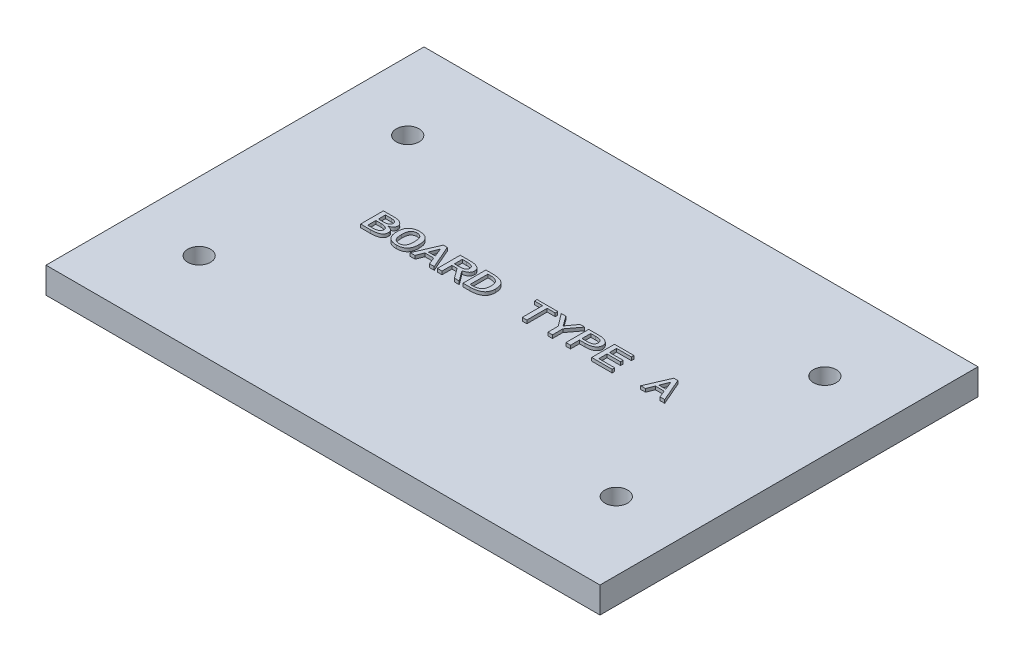
SolidWorks part; units mm, degrees
ref_plane "前视基准面" through (0, 0, 0) normal (0, 0, 1) x (1, 0, 0)
ref_plane "上视基准面" through (0, 0, 0) normal (0, 1, 0) x (1, 0, 0)
ref_plane "右视基准面" through (0, 0, 0) normal (1, 0, 0) x (0, 0, -1)
sketch "草图1" plane through (0, 0, 0) normal (0, 1, 0) x (1, 0, 0)
  line L1 (-42.5, 29) -> (42.5, 29)
  line L2 (-42.5, 29) -> (-42.5, -29)
  line L3 (-42.5, -29) -> (42.5, -29)
  line L4 (42.5, 29) -> (42.5, -29)
  line L5 (-42.5, 29) -> (23.4483, -16) construction
  line L11 (-30.4348, 15.2174) -> (0, 0) construction
  line L12 (-30.4348, -15.2174) -> (0, 0) construction
  circle A0 centre (-32, 16) radius 1.75
  circle A1 centre (32, 16) radius 1.75
  circle A2 centre (-32, -16) radius 1.75
  circle A3 centre (32, -16) radius 1.75
  point P0 (0, 0)
  point P6 (0, 0)
  dimension "D5" = 3.5
  dimension "D6" = 3.5
  dimension "D7" = 3.5
  dimension "D8" = 3.5
  dimension "D1" = 58
  dimension "D2" = 32
  dimension "D3" = 85
  dimension "D4" = 64
extrude "凸台-拉伸1" add sketch "草图1" along normal blind 4
sketch "草图2" plane through (0, 4, 0) normal (0, 1, 0) x (1, 0, 0)
  line L1 (-21.7977, 0.1023) -> (-23.3328, 0.1023)
  line L2 (-23.3328, 0.1023) -> (-23.3328, 3.6023)
  line L3 (-23.3328, 3.6023) -> (-21.7363, 3.6023)
  line L4 (-21.706, 3.2135) -> (-22.627, 3.2135)
  line L5 (-22.627, 3.2135) -> (-22.627, 2.1287)
  line L6 (-22.627, 2.1287) -> (-21.7363, 2.1287)
  line L7 (-21.8288, 1.7398) -> (-22.627, 1.7398)
  line L8 (-22.627, 1.7398) -> (-22.627, 0.4912)
  line L9 (-22.627, 0.4912) -> (-21.9205, 0.4912)
  line L10 (-12.0345, 0.1023) -> (-12.7714, 0.1023)
  line L11 (-12.7714, 0.1023) -> (-13.2012, 1.1871)
  line L12 (-13.2012, 1.1871) -> (-14.5521, 1.1871)
  line L13 (-14.5521, 1.1871) -> (-14.9819, 0.1023)
  line L14 (-14.9819, 0.1023) -> (-15.7187, 0.1023)
  line L15 (-15.7187, 0.1023) -> (-14.1837, 3.6433)
  line L16 (-14.1837, 3.6433) -> (-13.5696, 3.6433)
  line L17 (-13.5696, 3.6433) -> (-12.0345, 0.1023)
  line L18 (-13.3551, 1.576) -> (-13.8463, 2.8246)
  line L19 (-13.8463, 2.8246) -> (-13.9077, 2.8246)
  line L20 (-13.9077, 2.8246) -> (-14.3989, 1.576)
  line L21 (-14.3989, 1.576) -> (-13.3551, 1.576)
  line L22 (-8.1972, 0.1023) -> (-8.934, 0.1023)
  line L23 (-8.934, 0.1023) -> (-10.0393, 1.617)
  line L24 (-10.0393, 1.617) -> (-10.8375, 1.617)
  line L25 (-10.8375, 1.617) -> (-10.8375, 0.1023)
  line L26 (-10.8375, 0.1023) -> (-11.5433, 0.1023)
  line L27 (-11.5433, 0.1023) -> (-11.5433, 3.6023)
  line L28 (-11.5433, 3.6023) -> (-10.0082, 3.6023)
  line L29 (-9.3639, 1.6784) -> (-8.1972, 0.1023)
  line L30 (-10.1621, 3.2135) -> (-10.8375, 3.2135)
  line L31 (-10.8375, 3.2135) -> (-10.8375, 2.0058)
  line L32 (-10.8375, 2.0058) -> (-9.9779, 2.0058)
  line L33 (-6.5696, 0.1023) -> (-7.6135, 0.1023)
  line L34 (-7.6135, 0.1023) -> (-7.6135, 3.6023)
  line L35 (-7.6135, 3.6023) -> (-6.5696, 3.6023)
  line L36 (-6.5696, 3.2135) -> (-6.9077, 3.2135)
  line L37 (-6.9077, 3.2135) -> (-6.9077, 0.4912)
  line L38 (-6.9077, 0.4912) -> (-6.5696, 0.4912)
  line L39 (3.4081, 3.2135) -> (2.18, 3.2135)
  line L40 (2.18, 3.2135) -> (2.18, 0.1023)
  line L41 (2.18, 0.1023) -> (1.4742, 0.1023)
  line L42 (1.4742, 0.1023) -> (1.4742, 3.2135)
  line L43 (1.4742, 3.2135) -> (0.2462, 3.2135)
  line L44 (0.2462, 3.2135) -> (0.2462, 3.6023)
  line L45 (0.2462, 3.6023) -> (3.4081, 3.6023)
  line L46 (3.4081, 3.6023) -> (3.4081, 3.2135)
  line L47 (7.5532, 3.6023) -> (6.1098, 1.6784)
  line L48 (6.1098, 1.6784) -> (6.1098, 0.1023)
  line L49 (6.1098, 0.1023) -> (5.4041, 0.1023)
  line L50 (5.4041, 0.1023) -> (5.4041, 1.6784)
  line L51 (5.4041, 1.6784) -> (3.9607, 3.6023)
  line L52 (3.9607, 3.6023) -> (4.6672, 3.6023)
  line L53 (4.6672, 3.6023) -> (5.7414, 2.1082)
  line L54 (5.7414, 2.1082) -> (5.7725, 2.1082)
  line L55 (5.7725, 2.1082) -> (6.8467, 3.6023)
  line L56 (6.8467, 3.6023) -> (7.5532, 3.6023)
  line L57 (9.7637, 1.4737) -> (8.873, 1.4737)
  line L58 (8.873, 1.4737) -> (8.873, 0.1023)
  line L59 (8.873, 0.1023) -> (8.1672, 0.1023)
  line L60 (8.1672, 0.1023) -> (8.1672, 3.6023)
  line L61 (8.1672, 3.6023) -> (9.7637, 3.6023)
  line L62 (9.5795, 3.2135) -> (8.873, 3.2135)
  line L63 (8.873, 3.2135) -> (8.873, 1.8626)
  line L64 (8.873, 1.8626) -> (9.5795, 1.8626)
  line L65 (15.2589, 0.1023) -> (12.1274, 0.1023)
  line L66 (12.1274, 0.1023) -> (12.1274, 3.6023)
  line L67 (12.1274, 3.6023) -> (15.1058, 3.6023)
  line L68 (15.1058, 3.6023) -> (15.1058, 3.2135)
  line L69 (15.1058, 3.2135) -> (12.8339, 3.2135)
  line L70 (12.8339, 3.2135) -> (12.8339, 2.1287)
  line L71 (12.8339, 2.1287) -> (14.9216, 2.1287)
  line L72 (14.9216, 2.1287) -> (14.9216, 1.7398)
  line L73 (14.9216, 1.7398) -> (12.8339, 1.7398)
  line L74 (12.8339, 1.7398) -> (12.8339, 0.4912)
  line L75 (12.8339, 0.4912) -> (15.2589, 0.4912)
  line L76 (15.2589, 0.4912) -> (15.2589, 0.1023)
  line L77 (23.3339, 0.1023) -> (22.597, 0.1023)
  line L78 (22.597, 0.1023) -> (22.1672, 1.1871)
  line L79 (22.1672, 1.1871) -> (20.8163, 1.1871)
  line L80 (20.8163, 1.1871) -> (20.3865, 0.1023)
  line L81 (20.3865, 0.1023) -> (19.6497, 0.1023)
  line L82 (19.6497, 0.1023) -> (21.1848, 3.6433)
  line L83 (21.1848, 3.6433) -> (21.7988, 3.6433)
  line L84 (21.7988, 3.6433) -> (23.3339, 0.1023)
  line L85 (22.0133, 1.576) -> (21.5221, 2.8246)
  line L86 (21.5221, 2.8246) -> (21.4607, 2.8246)
  line L87 (21.4607, 2.8246) -> (20.9695, 1.576)
  line L88 (20.9695, 1.576) -> (22.0133, 1.576)
  spline S0 degree 3 poles (-20.0481, 1.1462) (-20.0483, 1.0544) (-20.0603, 0.9197) (-20.1134, 0.7533) (-20.168, 0.6439) (-20.2374, 0.5458) (-20.3231, 0.4597) (-20.4244, 0.3858) (-20.5405, 0.3245) (-20.6677, 0.2723) (-20.8038, 0.2269) (-20.9484, 0.1883) (-21.1015, 0.1565) (-21.2635, 0.1326) (-21.4962, 0.109) (-21.6755, 0.1026) (-21.7977, 0.1023) knots 0 0 0 0 0.119736 0.174373 0.226618 0.278301 0.330193 0.384099 0.440934 0.500827 0.562954 0.627693 0.695589 0.766471 0.8409 1 1 1 1
  spline S1 degree 3 poles (-21.7363, 3.6023) (-21.6163, 3.6035) (-21.4419, 3.5947) (-21.2179, 3.5677) (-21.0678, 3.538) (-20.9295, 3.5011) (-20.8029, 3.4559) (-20.6883, 3.4016) (-20.5861, 3.339) (-20.4962, 3.2708) (-20.4175, 3.1995) (-20.3505, 3.125) (-20.2968, 3.0464) (-20.253, 2.9656) (-20.2137, 2.8516) (-20.2009, 2.762) (-20.2012, 2.7018) knots 0 0 0 0 0.182524 0.265464 0.343062 0.415165 0.483037 0.547362 0.60777 0.66514 0.71876 0.76915 0.817253 0.86335 0.90859 1 1 1 1
  spline S2 degree 3 poles (-20.2012, 2.7018) (-20.2005, 2.644) (-20.2084, 2.5596) (-20.2368, 2.4536) (-20.2641, 2.3816) (-20.3024, 2.3168) (-20.3468, 2.2569) (-20.401, 2.2041) (-20.4825, 2.1429) (-20.5918, 2.0786) (-20.7674, 1.9905) (-20.9062, 1.9451) (-20.9994, 1.924) knots 0 0 0 0 0.142117 0.207166 0.27002 0.331065 0.391916 0.453072 0.516539 0.642453 0.764608 1 1 1 1
  spline S3 degree 3 poles (-20.9994, 1.924) (-20.8799, 1.9052) (-20.706, 1.8575) (-20.4887, 1.7603) (-20.3636, 1.6861) (-20.2719, 1.6192) (-20.2121, 1.564) (-20.161, 1.5051) (-20.1194, 1.4413) (-20.0875, 1.3734) (-20.0563, 1.2759) (-20.0481, 1.1984) (-20.0481, 1.1462) knots 0 0 0 0 0.271119 0.402277 0.532922 0.596518 0.656684 0.714966 0.77109 0.826871 0.882798 1 1 1 1
  spline S4 degree 3 poles (-20.9077, 2.7018) (-20.9083, 2.7434) (-20.9137, 2.8051) (-20.9389, 2.8814) (-20.964, 2.933) (-20.9971, 2.9795) (-21.0372, 3.0218) (-21.0842, 3.0598) (-21.1579, 3.1032) (-21.261, 3.1484) (-21.4498, 3.2015) (-21.6019, 3.2132) (-21.706, 3.2135) knots 0 0 0 0 0.117826 0.172575 0.225787 0.27896 0.332887 0.389634 0.448774 0.573488 0.706095 1 1 1 1
  spline S5 degree 3 poles (-21.7363, 2.1287) (-21.6308, 2.1285) (-21.4761, 2.1432) (-21.2824, 2.1995) (-21.1736, 2.2474) (-21.096, 2.296) (-21.0448, 2.3368) (-21.003, 2.3849) (-20.9674, 2.4372) (-20.941, 2.4961) (-20.9137, 2.5834) (-20.9079, 2.654) (-20.9077, 2.7018) knots 0 0 0 0 0.27897 0.406954 0.531511 0.591504 0.648419 0.703734 0.759081 0.814925 0.873612 1 1 1 1
  spline S6 degree 3 poles (-20.7849, 1.1462) (-20.7851, 1.1972) (-20.794, 1.2725) (-20.8285, 1.3649) (-20.8638, 1.4267) (-20.9098, 1.4817) (-20.9664, 1.5297) (-21.0322, 1.5727) (-21.1346, 1.6201) (-21.2736, 1.6679) (-21.5134, 1.7251) (-21.7014, 1.7396) (-21.8288, 1.7398) knots 0 0 0 0 0.114531 0.16774 0.219986 0.273047 0.327639 0.385741 0.448541 0.579968 0.714406 1 1 1 1
  spline S7 degree 3 poles (-21.9205, 0.4912) (-21.8338, 0.4914) (-21.7076, 0.4948) (-21.5453, 0.5109) (-21.4355, 0.525) (-21.3342, 0.5462) (-21.2404, 0.5697) (-21.1552, 0.5994) (-21.0775, 0.6324) (-21.0086, 0.6717) (-20.9484, 0.7185) (-20.8974, 0.7724) (-20.8556, 0.8335) (-20.8236, 0.9019) (-20.7927, 1.0057) (-20.7848, 1.0892) (-20.7849, 1.1462) knots 0 0 0 0 0.174988 0.254371 0.328987 0.39817 0.462958 0.523897 0.580057 0.633043 0.683521 0.733285 0.782066 0.832234 0.884967 1 1 1 1
  spline S8 degree 3 poles (-16.1182, 1.8626) (-16.1179, 1.7131) (-16.1298, 1.4964) (-16.1774, 1.2212) (-16.2257, 1.0391) (-16.2872, 0.8734) (-16.3644, 0.7251) (-16.4548, 0.593) (-16.5606, 0.4787) (-16.6784, 0.3795) (-16.8075, 0.2944) (-16.947, 0.2222) (-17.0975, 0.1625) (-17.2595, 0.1176) (-17.4959, 0.0731) (-17.6805, 0.0617) (-17.8065, 0.0614) knots 0 0 0 0 0.158122 0.228967 0.295107 0.357119 0.415586 0.471497 0.525982 0.579856 0.634053 0.689172 0.745811 0.804966 0.866726 1 1 1 1
  spline S9 degree 3 poles (-17.8065, 0.0614) (-17.9329, 0.0618) (-18.1183, 0.0731) (-18.3559, 0.1177) (-18.5194, 0.1626) (-18.6721, 0.2223) (-18.8145, 0.2943) (-18.9466, 0.3797) (-19.0681, 0.4783) (-19.1769, 0.5931) (-19.2715, 0.7245) (-19.3506, 0.8733) (-19.4145, 1.039) (-19.4655, 1.2209) (-19.5134, 1.4964) (-19.5268, 1.713) (-19.5258, 1.8626) knots 0 0 0 0 0.132825 0.194394 0.253627 0.310592 0.366251 0.420939 0.475439 0.53025 0.586517 0.644927 0.706771 0.772637 0.84301 1 1 1 1
  spline S10 degree 3 poles (-19.5258, 1.8626) (-19.526, 1.9399) (-19.5229, 2.0539) (-19.5107, 2.2027) (-19.4977, 2.3078) (-19.4821, 2.4088) (-19.4622, 2.5054) (-19.439, 2.5978) (-19.4115, 2.6857) (-19.3814, 2.7694) (-19.3471, 2.8486) (-19.3092, 2.9235) (-19.2683, 2.9947) (-19.2228, 3.0611) (-19.1742, 3.1233) (-19.1226, 3.1817) (-19.0472, 3.2519) (-18.9467, 3.3329) (-18.8142, 3.4156) (-18.6721, 3.4863) (-18.5192, 3.5442) (-18.3559, 3.5886) (-18.1182, 3.6317) (-17.933, 3.6441) (-17.8065, 3.6433) knots 0 0 0 0 0.081613 0.120129 0.157456 0.193347 0.227902 0.261455 0.29383 0.325029 0.355235 0.384798 0.413464 0.441854 0.469581 0.496764 0.523916 0.578158 0.632662 0.688332 0.745362 0.80479 0.866586 1 1 1 1
  spline S11 degree 3 poles (-17.8065, 3.6433) (-17.6805, 3.6443) (-17.496, 3.6316) (-17.2595, 3.5887) (-17.0977, 3.5443) (-16.9471, 3.4864) (-16.8078, 3.4155) (-16.6785, 3.3329) (-16.561, 3.2359) (-16.4543, 3.1246) (-16.3644, 2.9939) (-16.2874, 2.8474) (-16.2254, 2.6833) (-16.1775, 2.5024) (-16.1297, 2.228) (-16.1179, 2.0117) (-16.1182, 1.8626) knots 0 0 0 0 0.133901 0.195907 0.255272 0.311987 0.367123 0.421138 0.474753 0.528713 0.58445 0.64272 0.704275 0.770471 0.841391 1 1 1 1
  spline S12 degree 3 poles (-16.8551, 1.8626) (-16.8554, 1.9936) (-16.862, 2.1814) (-16.8909, 2.4184) (-16.9206, 2.5692) (-16.9598, 2.7014) (-17.006, 2.8158) (-17.0621, 2.9118) (-17.1288, 2.9889) (-17.2019, 3.0506) (-17.2759, 3.1065) (-17.3552, 3.1516) (-17.438, 3.1891) (-17.5244, 3.2191) (-17.6472, 3.246) (-17.7421, 3.2555) (-17.8065, 3.2544) knots 0 0 0 0 0.203754 0.291659 0.371016 0.44236 0.50576 0.56249 0.614305 0.663309 0.711083 0.758251 0.804842 0.852176 0.900114 1 1 1 1
  spline S13 degree 3 poles (-17.8065, 3.2544) (-17.8713, 3.2555) (-17.967, 3.246) (-18.0911, 3.219) (-18.1791, 3.1888) (-18.2645, 3.1517) (-18.3469, 3.1063) (-18.4246, 3.051) (-18.5007, 2.989) (-18.5705, 2.912) (-18.6296, 2.8161) (-18.6793, 2.7018) (-18.7195, 2.5692) (-18.7509, 2.4185) (-18.7821, 2.1815) (-18.7887, 1.9936) (-18.7889, 1.8626) knots 0 0 0 0 0.099622 0.147441 0.195019 0.242546 0.290578 0.339435 0.389113 0.441417 0.498369 0.561725 0.632554 0.711243 0.798335 1 1 1 1
  spline S14 degree 3 poles (-18.7889, 1.8626) (-18.7887, 1.7313) (-18.7821, 1.5429) (-18.7508, 1.3049) (-18.7196, 1.1531) (-18.6792, 1.0193) (-18.6292, 0.9036) (-18.5708, 0.805) (-18.5007, 0.7257) (-18.4249, 0.6612) (-18.3467, 0.6047) (-18.2648, 0.5567) (-18.1793, 0.518) (-18.0911, 0.4873) (-17.9672, 0.4588) (-17.8712, 0.4505) (-17.8065, 0.4503) knots 0 0 0 0 0.20062 0.287477 0.366364 0.43706 0.500673 0.558534 0.611334 0.66141 0.710367 0.758632 0.806137 0.853502 0.901068 1 1 1 1
  spline S15 degree 3 poles (-17.8065, 0.4503) (-17.7422, 0.4505) (-17.647, 0.4588) (-17.5243, 0.4872) (-17.4378, 0.5177) (-17.355, 0.5568) (-17.2761, 0.6045) (-17.2016, 0.6616) (-17.1288, 0.7258) (-17.0618, 0.8052) (-17.0065, 0.9038) (-16.9599, 1.0197) (-16.9205, 1.1532) (-16.891, 1.305) (-16.862, 1.543) (-16.8555, 1.7313) (-16.8551, 1.8626) knots 0 0 0 0 0.099176 0.146853 0.193971 0.240551 0.287972 0.335864 0.385289 0.43762 0.495282 0.558942 0.630141 0.709686 0.797338 1 1 1 1
  spline S16 degree 3 poles (-10.0082, 3.6023) (-9.8912, 3.6015) (-9.7191, 3.5968) (-9.4967, 3.5706) (-9.3426, 3.545) (-9.1968, 3.5128) (-9.0599, 3.4717) (-8.9313, 3.4243) (-8.812, 3.3692) (-8.7036, 3.3066) (-8.6084, 3.2338) (-8.5285, 3.1509) (-8.4629, 3.0583) (-8.4117, 2.957) (-8.363, 2.8048) (-8.3495, 2.6828) (-8.3503, 2.5994) knots 0 0 0 0 0.161276 0.236592 0.308212 0.376337 0.442061 0.50482 0.565067 0.622775 0.676854 0.729517 0.780687 0.832506 0.885214 1 1 1 1
  spline S17 degree 3 poles (-8.3503, 2.5994) (-8.3502, 2.5346) (-8.3583, 2.439) (-8.3916, 2.3185) (-8.4251, 2.2356) (-8.4685, 2.1585) (-8.5224, 2.0877) (-8.5847, 2.0218) (-8.6571, 1.9636) (-8.7348, 1.9104) (-8.816, 1.8616) (-8.9004, 1.8187) (-8.9871, 1.7794) (-9.0772, 1.7465) (-9.202, 1.7084) (-9.2986, 1.689) (-9.3639, 1.6784) knots 0 0 0 0 0.12938 0.190057 0.248861 0.307339 0.366033 0.42595 0.487931 0.551011 0.61388 0.676799 0.739772 0.803747 0.868031 1 1 1 1
  spline S18 degree 3 poles (-9.0568, 2.5994) (-9.0566, 2.645) (-9.0639, 2.7128) (-9.0918, 2.7977) (-9.1207, 2.8564) (-9.1579, 2.911) (-9.2026, 2.9621) (-9.2568, 3.0083) (-9.3183, 3.0519) (-9.3895, 3.0907) (-9.4704, 3.1239) (-9.561, 3.1517) (-9.6617, 3.1741) (-9.7725, 3.1923) (-9.9403, 3.2096) (-10.0716, 3.2137) (-10.1621, 3.2135) knots 0 0 0 0 0.096696 0.14292 0.188895 0.234783 0.282583 0.332298 0.385329 0.44212 0.503571 0.570296 0.642775 0.721997 0.808148 1 1 1 1
  spline S19 degree 3 poles (-9.9779, 2.0058) (-9.862, 2.0058) (-9.6923, 2.0205) (-9.478, 2.0766) (-9.3568, 2.1248) (-9.2686, 2.1726) (-9.2117, 2.2154) (-9.1641, 2.2648) (-9.1241, 2.3196) (-9.0935, 2.3811) (-9.0646, 2.4739) (-9.057, 2.5485) (-9.0568, 2.5994) knots 0 0 0 0 0.281863 0.411533 0.537506 0.598025 0.655049 0.709802 0.764376 0.819336 0.876081 1 1 1 1
  spline S20 degree 3 poles (-4.3591, 1.8421) (-4.3595, 1.7665) (-4.3626, 1.6546) (-4.3796, 1.5093) (-4.395, 1.4062) (-4.4165, 1.3076) (-4.442, 1.2128) (-4.4724, 1.1225) (-4.5073, 1.0362) (-4.5474, 0.9544) (-4.5925, 0.8771) (-4.6407, 0.803) (-4.6947, 0.7338) (-4.7543, 0.6696) (-4.817, 0.6085) (-4.8851, 0.5522) (-4.9825, 0.4825) (-5.1146, 0.4046) (-5.2843, 0.3234) (-5.4667, 0.254) (-5.6628, 0.1995) (-5.8711, 0.1553) (-6.1743, 0.1135) (-6.4091, 0.1019) (-6.5696, 0.1023) knots 0 0 0 0 0.070517 0.104185 0.136374 0.167704 0.198225 0.227803 0.256548 0.284892 0.312654 0.340034 0.367227 0.394408 0.421568 0.448838 0.476692 0.533219 0.591494 0.651967 0.714912 0.781129 0.850366 1 1 1 1
  spline S21 degree 3 poles (-6.5696, 3.6023) (-6.4781, 3.602) (-6.343, 3.6001) (-6.1662, 3.5885) (-6.0406, 3.5774) (-5.9195, 3.5629) (-5.8032, 3.5456) (-5.6913, 3.5253) (-5.5844, 3.5009) (-5.4822, 3.4739) (-5.3847, 3.4432) (-5.2915, 3.4105) (-5.2036, 3.3727) (-5.1197, 3.3337) (-5.0407, 3.2905) (-4.9667, 3.2432) (-4.8963, 3.1941) (-4.8307, 3.1409) (-4.7702, 3.0828) (-4.7128, 3.0216) (-4.6608, 2.9552) (-4.6118, 2.8855) (-4.5682, 2.8108) (-4.5278, 2.7328) (-4.4918, 2.6504) (-4.4614, 2.5634) (-4.4338, 2.4727) (-4.4103, 2.3779) (-4.3914, 2.2787) (-4.3773, 2.1754) (-4.3625, 2.0297) (-4.3597, 1.9179) (-4.3591, 1.8421) knots 0 0 0 0 0.084205 0.124284 0.163043 0.20028 0.236488 0.271243 0.304865 0.337355 0.368539 0.398917 0.428199 0.456493 0.484071 0.511038 0.537232 0.563018 0.588677 0.614348 0.640169 0.66623 0.692711 0.719647 0.747037 0.775428 0.804338 0.834286 0.865299 0.897231 0.930181 1 1 1 1
  spline S22 degree 3 poles (-5.0959, 1.8421) (-5.0971, 1.959) (-5.1047, 2.129) (-5.1444, 2.3438) (-5.1839, 2.4851) (-5.2365, 2.6116) (-5.2994, 2.7249) (-5.3751, 2.8236) (-5.4627, 2.9088) (-5.5621, 2.9812) (-5.6723, 3.0437) (-5.7938, 3.0964) (-5.9268, 3.1398) (-6.0713, 3.1725) (-6.286, 3.206) (-6.4542, 3.2135) (-6.5696, 3.2135) knots 0 0 0 0 0.150566 0.218014 0.280566 0.338998 0.39387 0.446724 0.498443 0.550516 0.604379 0.661145 0.720659 0.784051 0.851492 1 1 1 1
  spline S23 degree 3 poles (-6.5696, 0.4912) (-6.4543, 0.4917) (-6.2861, 0.4982) (-6.0713, 0.5306) (-5.927, 0.5627) (-5.7941, 0.6046) (-5.6724, 0.6549) (-5.5621, 0.7151) (-5.4631, 0.7852) (-5.3747, 0.8674) (-5.2996, 0.9647) (-5.2363, 1.0765) (-5.1841, 1.2019) (-5.1444, 1.3419) (-5.1045, 1.5557) (-5.0972, 1.7252) (-5.0959, 1.8421) knots 0 0 0 0 0.149276 0.217027 0.280685 0.340318 0.397002 0.450674 0.502451 0.553543 0.606163 0.66076 0.719203 0.781462 0.848629 1 1 1 1
  spline S24 degree 3 poles (11.3905, 2.538) (11.3899, 2.46) (11.3791, 2.3437) (11.3323, 2.198) (11.2845, 2.0969) (11.2249, 2.0011) (11.1491, 1.9138) (11.0613, 1.8321) (10.9602, 1.7574) (10.8476, 1.6901) (10.7234, 1.6324) (10.5893, 1.5833) (10.4442, 1.5434) (10.289, 1.5114) (10.0613, 1.4822) (9.8847, 1.4733) (9.7637, 1.4737) knots 0 0 0 0 0.107788 0.159332 0.21012 0.261617 0.314236 0.36894 0.426681 0.487123 0.549441 0.615107 0.683802 0.756677 0.833265 1 1 1 1
  spline S25 degree 3 poles (9.7637, 3.6023) (9.8847, 3.6026) (10.0613, 3.5941) (10.2889, 3.5643) (10.4444, 3.5339) (10.5891, 3.4925) (10.7235, 3.4437) (10.8476, 3.3859) (10.9602, 3.3186) (11.0613, 3.2439) (11.1492, 3.1622) (11.2246, 3.075) (11.285, 2.9796) (11.3321, 2.8782) (11.3792, 2.7324) (11.3898, 2.616) (11.3905, 2.538) knots 0 0 0 0 0.166727 0.243312 0.316115 0.3849 0.450564 0.512878 0.573317 0.631056 0.685757 0.738374 0.789574 0.840675 0.892217 1 1 1 1
  spline S26 degree 3 poles (10.6848, 2.538) (10.6846, 2.598) (10.6773, 2.6852) (10.6484, 2.7943) (10.6179, 2.8657) (10.5783, 2.9289) (10.5303, 2.9847) (10.4739, 3.033) (10.4074, 3.0723) (10.3329, 3.1052) (10.2511, 3.1351) (10.16, 3.1587) (10.0607, 3.1796) (9.9525, 3.1938) (9.7914, 3.21) (9.666, 3.2132) (9.5795, 3.2135) knots 0 0 0 0 0.121457 0.176061 0.227851 0.277957 0.326564 0.376282 0.427694 0.482184 0.540926 0.603966 0.67239 0.746257 0.824903 1 1 1 1
  spline S27 degree 3 poles (9.5795, 1.8626) (9.666, 1.8628) (9.7914, 1.866) (9.9525, 1.8822) (10.0607, 1.8964) (10.16, 1.9173) (10.2511, 1.9409) (10.3329, 1.9709) (10.4074, 2.0038) (10.4739, 2.043) (10.5303, 2.0913) (10.5783, 2.1471) (10.6179, 2.2103) (10.6484, 2.2817) (10.6773, 2.3908) (10.6846, 2.4781) (10.6848, 2.538) knots 0 0 0 0 0.175097 0.253743 0.32761 0.396034 0.459074 0.517816 0.572306 0.623718 0.673436 0.722043 0.772149 0.823939 0.878543 1 1 1 1
extrude "凸台-拉伸2" add sketch "草图2" along normal blind 0.5
